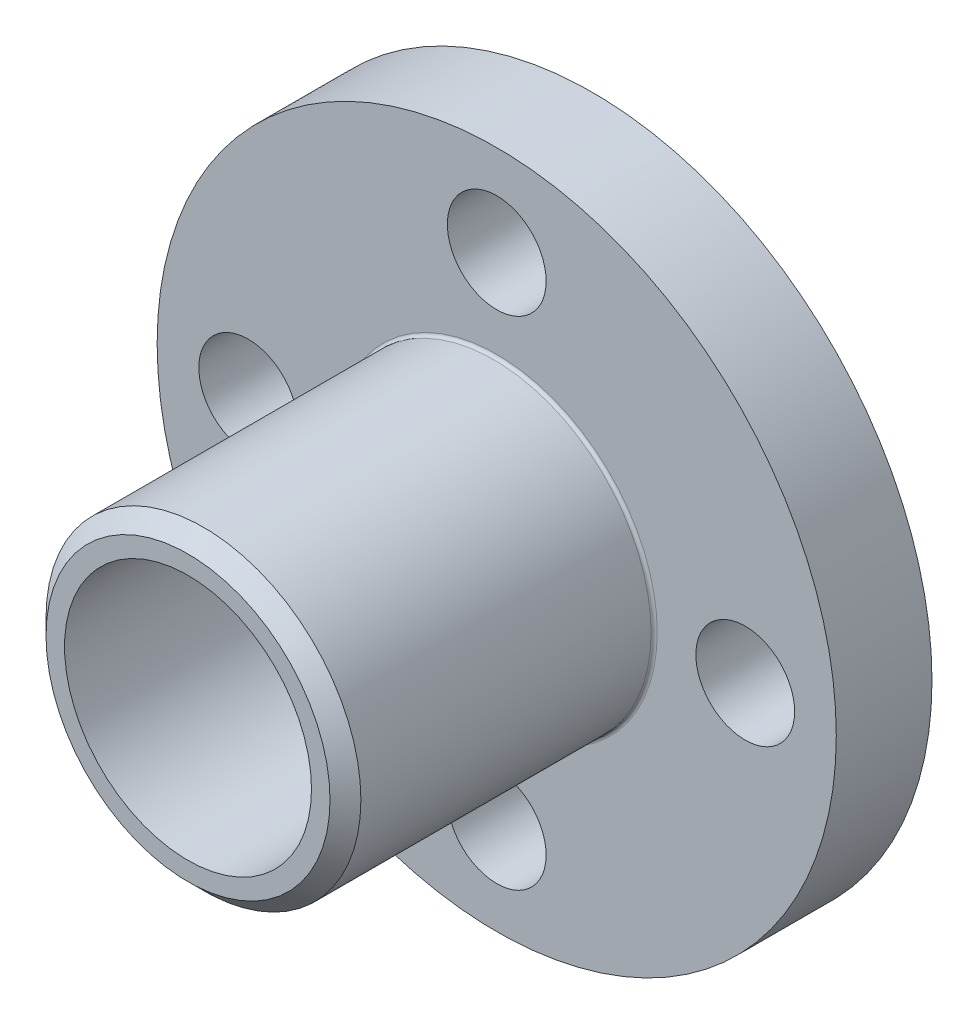
SolidWorks part; units mm, degrees
ref_plane "Front Plane" through (0, 0, 0) normal (0, 0, 1) x (1, 0, 0)
ref_plane "Top Plane" through (0, 0, 0) normal (0, 1, 0) x (1, 0, 0)
ref_plane "Right Plane" through (0, 0, 0) normal (1, 0, 0) x (0, 0, -1)
sketch "Sketch1" plane through (0, 0, 0) normal (0, 0, 1) x (1, 0, 0)
  circle A0 centre (0, 0) radius 5.075
  circle A1 centre (0, 0) radius 11
  dimension "D1" = 22
  dimension "D2" = 10.15
extrude "Boss-Extrude1" add sketch "Sketch1" along normal blind 3.1
sketch "Sketch2" plane through (0, 0, 3.1) normal (0, 0, 1) x (1, 0, 0)
  circle A0 centre (0, 0) radius 5.1
  circle A1 centre (0, 0) radius 4
  dimension "D1" = 10.2
  dimension "D2" = 8
extrude "Boss-Extrude2" add sketch "Sketch2" along normal blind 10 and the other way blind 3.1
chamfer "Chamfer1" distance 0.5 1 edges at (5.1, 0, 13.1)
fillet "Fillet1" radius 0.1 1 edges at (5.1, 0, 3.1)
sketch "Sketch3" plane through (0, 0, 3.1) normal (0, 0, 1) x (1, 0, 0)
  line L0 (0, 11) -> (0, 5.1) construction
  line L1 (-11, 0) -> (-5.1, 0) construction
  line L2 (0, -5.1) -> (0, -11) construction
  line L3 (5.1, 0) -> (11, 0) construction
  circle A0 centre (0, 0) radius 11 construction
  circle A1 centre (0, 0) radius 5.1 construction
  circle A2 centre (0, 8.05) radius 1.6
  circle A3 centre (8.05, 0) radius 1.6
  circle A4 centre (0, -8.05) radius 1.6
  circle A5 centre (-8.05, 0) radius 1.6
  dimension "D1" = 3.2
  dimension "D2" = 3.2
  dimension "D3" = 3.2
  dimension "D4" = 3.2
extrude "Cut-Extrude1" cut sketch "Sketch3" against normal blind 10
sketch "Sketch4" plane through (0, 0, 0) normal (0, 0, -1) x (-1, 0, 0)
  circle A2 centre (0, 0) radius 11
  circle A3 centre (0, 0) radius 11
  circle A5 centre (0, 0) radius 4
  circle A6 centre (0, 0) radius 4
  circle A8 centre (0, -8.05) radius 1.6
  circle A9 centre (0, -8.05) radius 1.6
  circle A11 centre (8.05, 0) radius 1.6
  circle A12 centre (8.05, 0) radius 1.6
  circle A14 centre (-8.05, 0) radius 1.6
  circle A15 centre (-8.05, 0) radius 1.6
  circle A17 centre (0, 8.05) radius 1.6
  circle A18 centre (0, 8.05) radius 1.6
  point P3 (0, 0)
  dimension "D1" = 0
  dimension "D2" = 0
  dimension "D3" = 0
  dimension "D4" = 0
  dimension "D5" = 0
  dimension "D6" = 0
